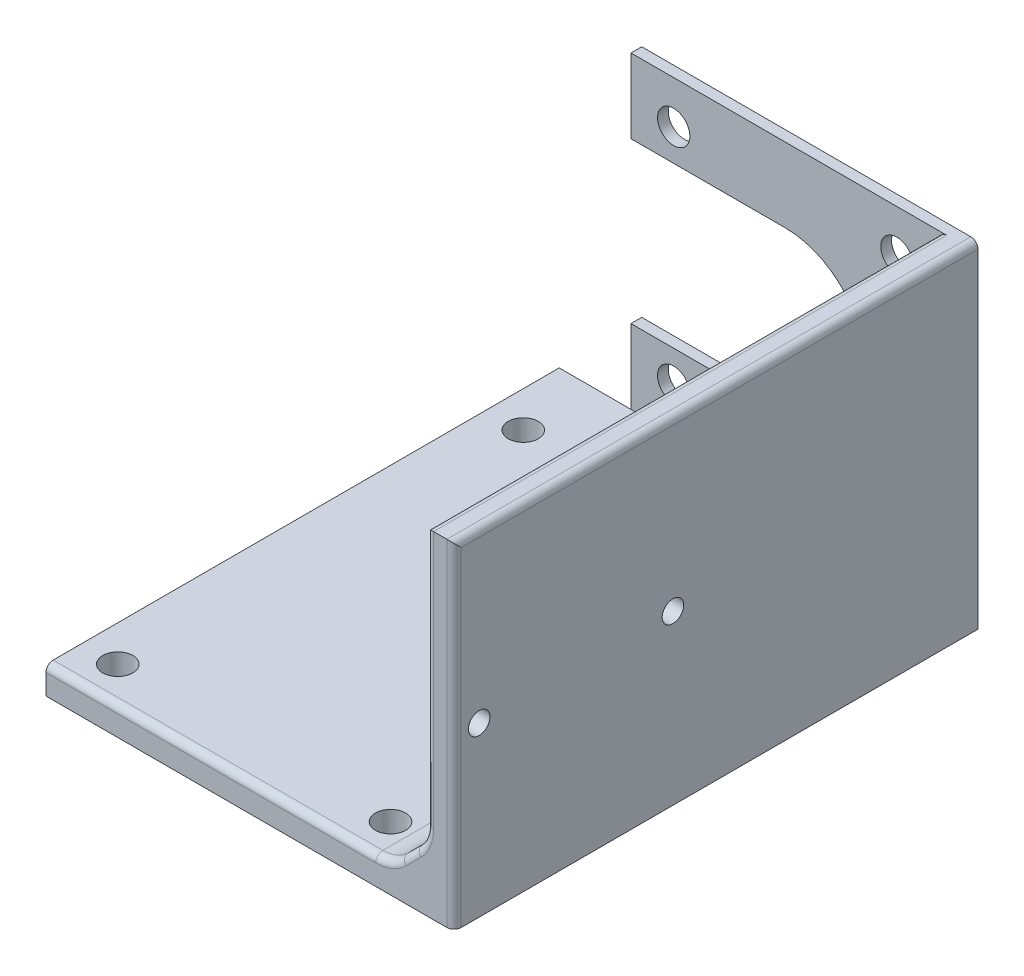
SolidWorks part; units mm, degrees
ref_plane "Plan de face" through (0, 0, 0) normal (0, 0, 1) x (1, 0, 0)
ref_plane "Plan de dessus" through (0, 0, 0) normal (0, 1, 0) x (1, 0, 0)
ref_plane "Plan de droite" through (0, 0, 0) normal (1, 0, 0) x (0, 0, -1)
sketch "Esquisse1" plane through (0, 0, 0) normal (0, 0, 1) x (1, 0, 0)
  line L0 (0, 0) -> (46.85, 0)
  line L1 (46.85, 0) -> (46.85, 46.85)
  line L2 (46.85, 46.85) -> (43, 46.85)
  line L3 (43, 46.85) -> (43, 3.85)
  line L4 (43, 3.85) -> (0, 3.85)
  line L5 (0, 3.85) -> (0, 0)
  dimension "D1" = 3.85
  dimension "D2" = 3.85
  dimension "D3" = 43
  dimension "D4" = 43
extrude "Boss.-Extru.1" add sketch "Esquisse1" along normal blind 39
sketch "Esquisse2" plane through (0, 0, 0) normal (0, 0, -1) x (-1, 0, 0)
  line L0 (-43, 25.35) -> (0, 25.35) construction
  line L1 (-43, 46.85) -> (0, 46.85)
  line L2 (-43, 46.85) -> (-43, 3.85)
  line L3 (-43, 3.85) -> (0, 3.85)
  line L4 (0, 46.85) -> (0, 3.85)
  line L5 (-21.5, 36.5) -> (0, 36.5)
  line L6 (-21.5, 14.2) -> (0, 14.2)
  line L8 (-37.05, 40.9) -> (-5.95, 40.9) construction
  line L9 (-37.05, 40.9) -> (-37.05, 9.8) construction
  line L10 (-37.05, 9.8) -> (-5.95, 9.8) construction
  line L11 (-5.95, 40.9) -> (-5.95, 9.8) construction
  arc A1 (-21.5, 36.5) -> (-21.5, 14.2) centre (-21.5, 25.35) ccw
  circle A2 centre (-5.95, 40.9) radius 2.25
  circle A3 centre (-37.05, 40.9) radius 2.25
  circle A4 centre (-37.05, 9.8) radius 2.25
  circle A5 centre (-5.95, 9.8) radius 2.25
  point P12 (-5.95, 25.35)
  line M9 (0, 3.85) -> (-43, 3.85)
  line M10 (-43, 3.85) -> (-43, 46.85)
  dimension "D1" = 31.1
  dimension "D5" = 11.15
  dimension "D8" = 4.5
  dimension "D9" = 4.5
  dimension "D10" = 4.5
  dimension "D11" = 4.5
  dimension "D2" = 31.1
  dimension "D3" = 0
  dimension "D4" = 15.55
  dimension "D6" = 21.5
  dimension "D7" = 21.5
extrude "Boss.-Extru.2" add sketch "Esquisse2" against normal blind 1.5 contours A1 L5 L4 L1 L6 A5 A4 A3 A2 M10 M9
sketch "Esquisse3" plane through (46.85, 0, 0) normal (1, 0, 0) x (0, 0, -1)
  line L0 (-39, 0) -> (0, 0) construction
  line L1 (-39, 46.85) -> (-73, 46.85)
  line L2 (-39, 46.85) -> (-39, 0)
  line L3 (-39, 0) -> (-73, 0)
  line L4 (-73, 46.85) -> (-73, 0)
  dimension "D1" = 34
  dimension "D2" = 0
extrude "Boss.-Extru.3" add sketch "Esquisse3" against normal up to surface (3.85 mm away) up to face at (43, 25.35, 20.25)
sketch "Esquisse4" plane through (46.85, 0, 0) normal (1, 0, 0) x (0, 0, -1)
  line L0 (-73, 23.425) -> (-39, 23.425) construction
  line L1 (-73, 46.85) -> (-73, 0) construction
  line L2 (-56, 23.425) -> (-42.5, 23.425) construction
  line L3 (-56, 23.425) -> (-69.5, 23.425) construction
  circle A0 centre (-69.5, 23.425) radius 1.5
  circle A1 centre (-42.5, 23.425) radius 1.5
  dimension "D4" = 3
  dimension "D5" = 3
  dimension "D1" = 34
  dimension "D2" = 13.5
  dimension "D3" = 13.5
extrude "Enlèv. mat.-Extru.1" cut sketch "Esquisse4" against normal blind 6.5
sketch "Esquisse5" plane through (0, 3.85, 0) normal (0, 1, 0) x (1, 0, 0)
  line L0 (0, -39) -> (0, -1.5) construction
  line L1 (43, -1.5) -> (-10, -1.5)
  line L2 (43, -1.5) -> (43, -73)
  line L3 (43, -73) -> (-10, -73)
  line L4 (-10, -1.5) -> (-10, -73)
  dimension "D1" = 71.5
  dimension "D2" = 10
extrude "Boss.-Extru.4" add sketch "Esquisse5" against normal up to surface (3.85 mm away) up to face at (29.95, 0, 37.3333)
sketch "Esquisse6" plane through (0, 3.85, 0) normal (0, 1, 0) x (1, 0, 0)
  line L0 (-5, -1.5) -> (-5, -68) construction
  line L1 (0, -1.5) -> (-10, -1.5) construction
  line L2 (-5, -68) -> (43, -68) construction
  line L3 (43, -73) -> (43, -1.5) construction
  line L4 (-10, -1.5) -> (-10, -73) construction
  line L5 (-10, -73) -> (43, -73) construction
  circle A0 centre (-5, -68) radius 2.1
  circle A1 centre (33, -68) radius 2.1
  circle A2 centre (-5, -11.5) radius 2.1
  dimension "D3" = 4.2
  dimension "D4" = 10
  dimension "D5" = 10
  dimension "D6" = 4.2
  dimension "D7" = 4.2
  dimension "D1" = 5
  dimension "D2" = 5
extrude "Enlèv. mat.-Extru.2" cut sketch "Esquisse6" against normal blind 6.5
sketch "Esquisse7" plane through (0, 0, 73) normal (0, 0, 1) x (1, 0, 0)
  line L0 (43, 3.85) -> (43, 8.85)
  line L1 (43, 3.85) -> (43, 46.85) construction
  line L2 (43, 8.85) -> (38, 3.85)
  line L3 (-10, 3.85) -> (43, 3.85) construction
  line L4 (38, 3.85) -> (43, 3.85)
  dimension "D1" = 5
  dimension "D2" = 5
extrude "Boss.-Extru.5" add sketch "Esquisse7" against normal blind 30
fillet "Congé1" radius 5 2 edges at (38, 3.85, 58) (43, 8.85, 58)
fillet "Congé2" radius 1 8 edges at (12.9645, 3.85, 73) (37.8423, 4.2306, 73) (40.5, 6.35, 73) (42.6194, 9.0077, 73) (43, 28.8855, 73) (46.85, 23.425, 73) (43, 46.85, 37.25) (46.85, 46.85, 36.5)
